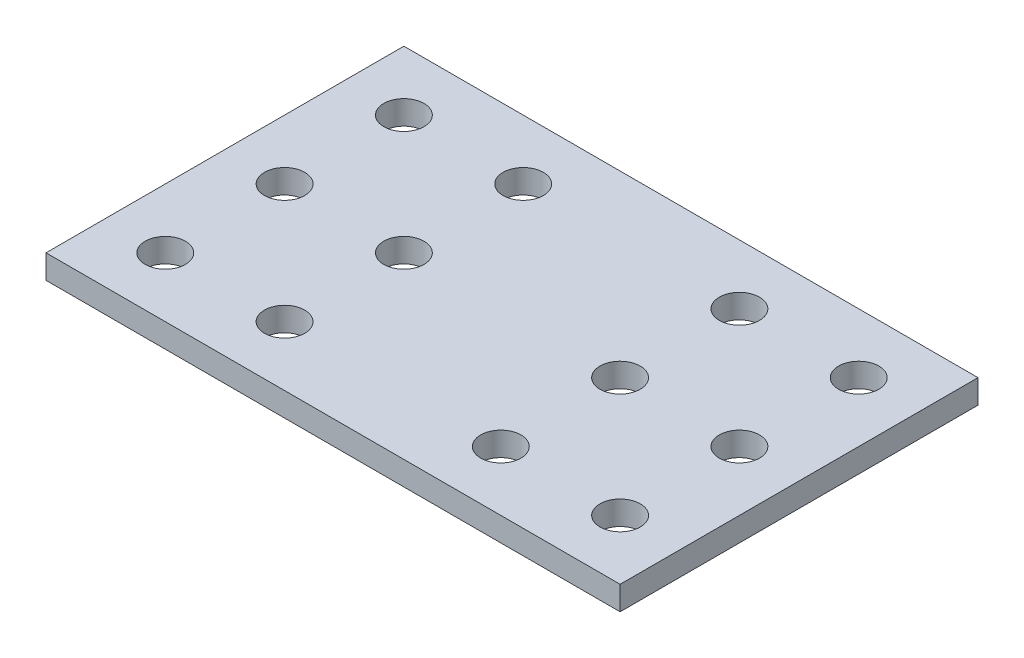
SolidWorks part; units mm, degrees
ref_plane "前视基准面" through (0, 0, 0) normal (0, 0, 1) x (1, 0, 0)
ref_plane "上视基准面" through (0, 0, 0) normal (0, 1, 0) x (1, 0, 0)
ref_plane "右视基准面" through (0, 0, 0) normal (1, 0, 0) x (0, 0, -1)
sketch "草图1" plane through (0, 0, 0) normal (0, 1, 0) x (1, 0, 0)
  line L1 (0, 0) -> (385, 0)
  line L2 (0, 0) -> (0, 240)
  line L3 (0, 240) -> (385, 240)
  line L4 (385, 0) -> (385, 240)
  dimension "D1" = 385
  dimension "D2" = 240
extrude "凸台-拉伸1" add sketch "草图1" along normal blind 16
sketch "草图2" plane through (0, 16, 0) normal (0, 1, 0) x (1, 0, 0)
  line L0 (192.5, -760) -> (192.5, 49240) construction
  line L1 (385, 240) -> (0, 240) construction
  line L2 (-1000, 120) -> (49000, 120) construction
  line L3 (0, 240) -> (0, 0) construction
  circle A0 centre (120, 120) radius 13.5
  point P5 (192.5, 240)
  point P12 (0, 120)
  dimension "D1" = 27
  dimension "D2" = 72.5
extrude "切除-拉伸1" cut sketch "草图2" against normal through all
pattern_linear "阵列(线性)1" count 2 spacing 80 along (0, 0, -1) of "切除-拉伸1"
pattern_linear "阵列(线性)2" count 2 spacing 80 along (0, 0, 1) of "切除-拉伸1"
pattern_linear "阵列(线性)3" count 2 spacing 80 along (-1, 0, 0) of "切除-拉伸1", "阵列(线性)1", "阵列(线性)2"
pattern_linear "阵列(线性)4" count 2 spacing 225 along (1, 0, 0) of "切除-拉伸1", "阵列(线性)1", "阵列(线性)2", "阵列(线性)3"
